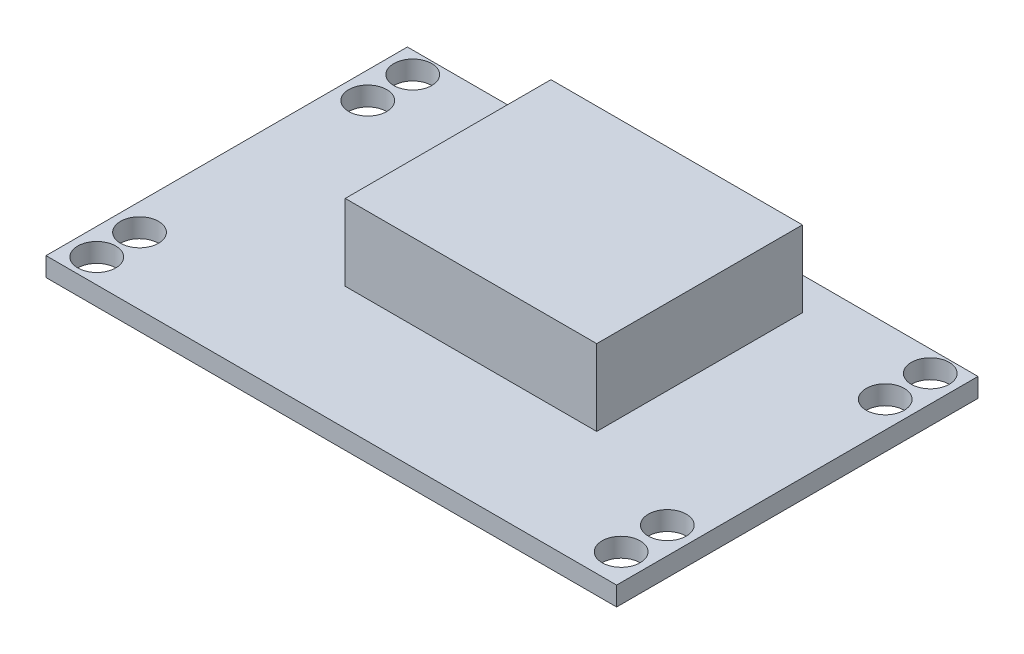
SolidWorks part; units mm, degrees
ref_plane "Front Plane" through (0, 0, 0) normal (0, 0, 1) x (1, 0, 0)
ref_plane "Top Plane" through (0, 0, 0) normal (0, 1, 0) x (1, 0, 0)
ref_plane "Right Plane" through (0, 0, 0) normal (1, 0, 0) x (0, 0, -1)
sketch "Sketch1" plane through (0, 0, 0) normal (0, 1, 0) x (1, 0, 0)
  line L1 (0, 0) -> (30, 0)
  line L2 (0, 0) -> (0, 19)
  line L3 (0, 19) -> (30, 19)
  line L4 (30, 0) -> (30, 19)
  dimension "D1" = 30
  dimension "D2" = 19
extrude "Boss-Extrude1" add sketch "Sketch1" along normal blind 1
sketch "Sketch2" plane through (0, 1, 0) normal (0, 1, 0) x (1, 0, 0)
  line L1 (9.2616, 17.2849) -> (22.4839, 17.2849)
  line L2 (9.2616, 17.2849) -> (9.2616, 6.4703)
  line L3 (9.2616, 6.4703) -> (22.4839, 6.4703)
  line L4 (22.4839, 17.2849) -> (22.4839, 6.4703)
extrude "Boss-Extrude2" add sketch "Sketch2" along normal blind 4
sketch "Sketch3" plane through (0, 1, 0) normal (0, 1, 0) x (1, 0, 0)
  circle A0 centre (1.3965, 17.8868) radius 1
  circle A1 centre (1.3965, 15.5193) radius 1
  circle A2 centre (1.3965, 3.5209) radius 1
  circle A3 centre (1.3965, 1.2737) radius 1
  circle A4 centre (28.6035, 1.6348) radius 1
  circle A5 centre (28.6035, 4.0626) radius 1
  circle A6 centre (28.6035, 17.8868) radius 1
  circle A7 centre (28.6035, 15.5193) radius 1
  point P16 (1.55, 1.4071)
  point P17 (1.5786, 3.6428)
  point P18 (1.5169, 6.2496)
  point P19 (1.4567, 1.2737)
  point P20 (1.3965, 3.5209)
  point P21 (1.3965, 15.5193)
  point P22 (1.3965, 17.8868)
  point P23 (28.6035, 15.9205)
  point P24 (28.6035, 18.0473)
  point P25 (28.6035, 15.5193)
  point P26 (28.6035, 17.8868)
  point P27 (28.6035, 4.0626)
  point P28 (28.6035, 1.6348)
  dimension "D1" = 2
extrude "Cut-Extrude1" cut sketch "Sketch3" against normal through all
